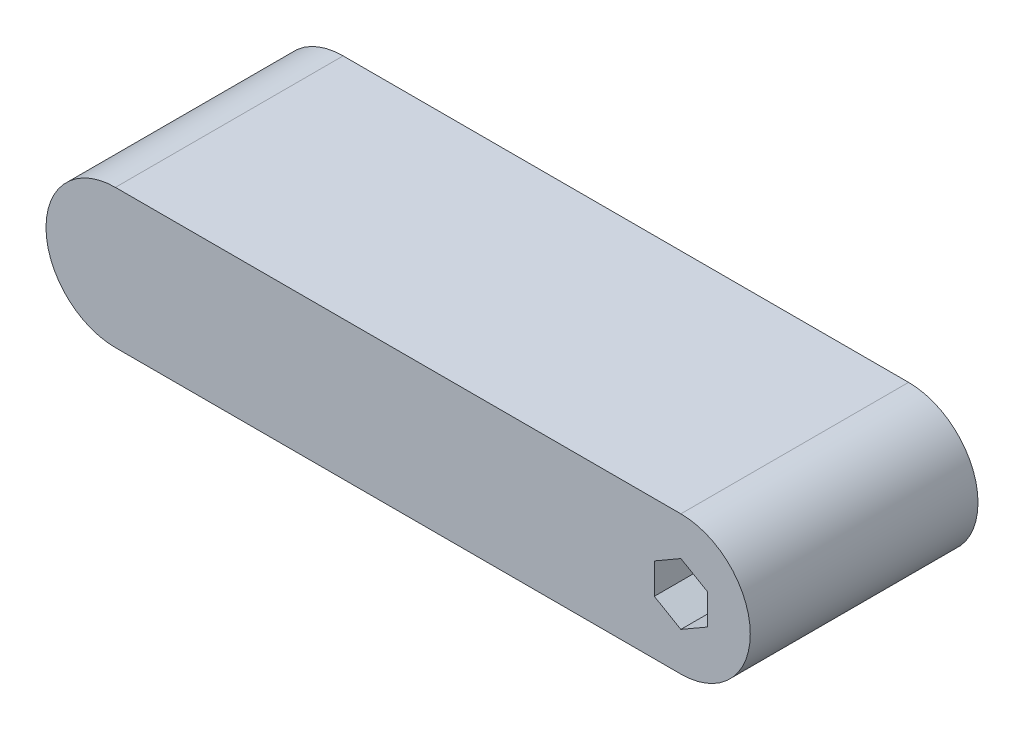
SolidWorks part; units mm, degrees
ref_plane "Front Plane" through (0, 0, 0) normal (0, 0, 1) x (1, 0, 0)
ref_plane "Top Plane" through (0, 0, 0) normal (0, 1, 0) x (1, 0, 0)
ref_plane "Right Plane" through (0, 0, 0) normal (1, 0, 0) x (0, 0, -1)
sketch "Sketch1" plane through (0, 0, 0) normal (0, 0, 1) x (1, 0, 0)
  line L0 (-6.4738, -12.5) -> (58.3471, -12.5) construction
  line L1 (0, -9.1432) -> (-74.4921, -9.1432)
  line L2 (15, -15) -> (-15, -15) construction
  line L3 (15, -15) -> (15, 15) construction
  line L4 (15, 15) -> (-15, 15) construction
  line L5 (-15, -15) -> (-15, 15) construction
  line L6 (15, -15) -> (-15, 15) construction
  line L7 (15, 15) -> (-15, -15) construction
  line L8 (0, 9.1432) -> (-74.4921, 9.1432)
  circle A0 centre (0, 0) radius 12.5 construction
  circle A1 centre (35.3553, 12.5) radius 25 construction
  arc A2 (0, -9.1432) -> (0, 9.1432) centre (0, 0) ccw
  arc A3 (-74.4921, 9.1432) -> (-74.4921, -9.1432) centre (-74.4921, 0) ccw
  dimension "D1" = 25
  dimension "D2" = 50
  dimension "D3" = 30
extrude "Boss-Extrude1" add sketch "Sketch1" along normal blind 30 contours L8 A3 L1 A2
sketch "Sketch2" plane through (0, 0, 30) normal (0, 0, 1) x (1, 0, 0)
  line L1 (-3.5, 2.0207) -> (-3.5, -2.0207)
  line L2 (-3.5, -2.0207) -> (0, -4.0415)
  line L3 (0, -4.0415) -> (3.5, -2.0207)
  line L4 (3.5, -2.0207) -> (3.5, 2.0207)
  line L5 (3.5, 2.0207) -> (0, 4.0415)
  line L6 (0, 4.0415) -> (-3.5, 2.0207)
  circle A0 centre (0, 0) radius 3.5 construction
  point P1 (0, 4.0415)
  dimension "D1" = 7
extrude "Cut-Extrude1" cut sketch "Sketch2" against normal through all
